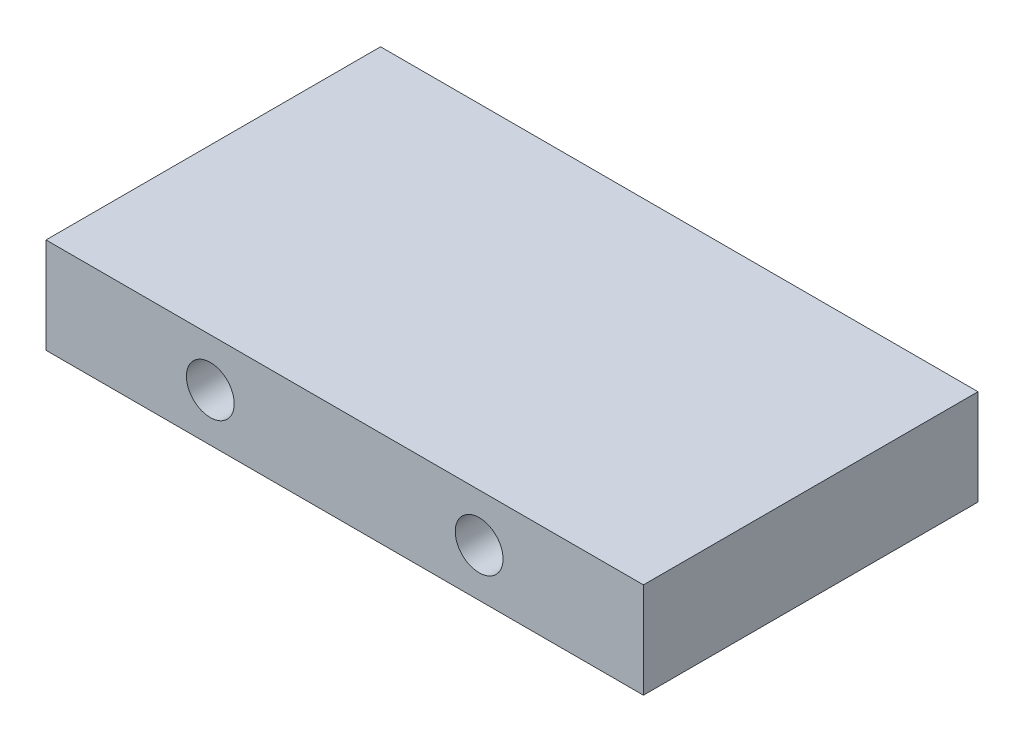
SolidWorks part; units mm, degrees
material "ABS"
ref_plane "Front Plane" through (0, 0, 0) normal (0, 0, 1) x (1, 0, 0)
ref_plane "Top Plane" through (0, 0, 0) normal (0, 1, 0) x (1, 0, 0)
ref_plane "Right Plane" through (0, 0, 0) normal (1, 0, 0) x (0, 0, -1)
sketch "Sketch1" plane through (0, 0, 0) normal (0, 0, 1) x (1, 0, 0)
  line L0 (-25, 0) -> (25, 0) construction
  line L1 (25, 4) -> (-25, 4)
  line L2 (25, 4) -> (25, -4)
  line L3 (25, -4) -> (-25, -4)
  line L4 (-25, 4) -> (-25, -4)
  line L5 (25, 4) -> (-25, -4) construction
  line L6 (25, -4) -> (-25, 4) construction
  circle A0 centre (-11.25, 0) radius 2
  circle A1 centre (11.25, 0) radius 2
  point P0 (0, 0)
  dimension "D3" = 22.5
  dimension "D4" = 11.25
  dimension "D5" = 4
  dimension "D6" = 4
  dimension "D1" = 8
  dimension "D2" = 50
extrude "Boss-Extrude1" add sketch "Sketch1" along normal blind 28
